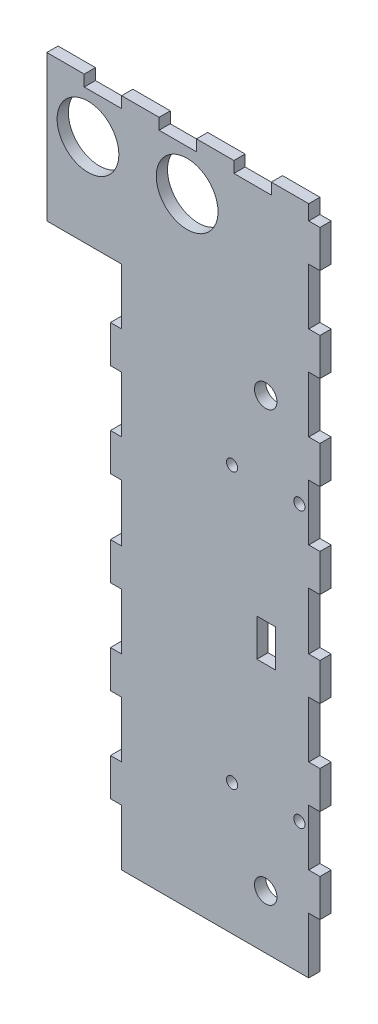
SolidWorks part; units mm, degrees
ref_plane "Plan de face" through (0, 0, 0) normal (0, 0, 1) x (1, 0, 0)
ref_plane "Plan de dessus" through (0, 0, 0) normal (0, 1, 0) x (1, 0, 0)
ref_plane "Plan de droite" through (0, 0, 0) normal (1, 0, 0) x (0, 0, -1)
sketch "Esquisse2" plane through (0, 0, 0) normal (0, 0, 1) x (1, 0, 0)
  line L3 (-71.7115, -86.2767) -> (-71.7115, -71.2767)
  line L4 (-71.7115, -21.2767) -> (-74.7115, -21.2767)
  line L5 (-74.7115, -21.2767) -> (-74.7115, -11.2767)
  line L6 (-74.7115, -11.2767) -> (-71.7115, -11.2767)
  line L7 (-71.7115, -11.2767) -> (-71.7115, 3.9701)
  line L8 (-71.7115, 3.9701) -> (-74.7115, 3.9701)
  line L9 (-74.7115, 3.9701) -> (-74.7115, 13.9701)
  line L10 (-74.7115, 13.9701) -> (-71.7115, 13.9701)
  line L11 (-71.7115, 13.9701) -> (-71.7115, 28.9701)
  line L12 (-71.7115, 28.9701) -> (-74.7115, 28.9701)
  line L13 (-74.7115, 28.9701) -> (-74.7115, 38.9701)
  line L14 (-74.7115, 38.9701) -> (-71.7115, 38.9701)
  line L15 (-71.7115, 38.9701) -> (-71.7115, 53.9701)
  line L16 (-71.7115, -36.2767) -> (-74.7115, -36.2767)
  line L17 (-74.7115, -36.2767) -> (-74.7115, -46.2767)
  line L18 (-74.7115, -46.2767) -> (-71.7115, -46.2767)
  line L19 (-71.7115, -61.2767) -> (-74.7115, -61.2767)
  line L20 (-74.7115, -61.2767) -> (-74.7115, -71.2767)
  line L21 (-74.7115, -71.2767) -> (-71.7115, -71.2767)
  line L22 (-71.7115, -61.2767) -> (-71.7115, -46.2767)
  line L23 (-71.7115, -36.2767) -> (-71.7115, -21.2767)
  line L24 (-71.7115, -86.2767) -> (-21.7115, -86.2767)
  line L26 (-46.7115, 53.7233) -> (-46.7115, -122.9745) construction
  line L27 (-21.7115, -36.2767) -> (-21.7115, -21.2767)
  line L28 (-21.7115, -61.2767) -> (-21.7115, -46.2767)
  line L29 (-18.7115, -71.2767) -> (-21.7115, -71.2767)
  line L30 (-18.7115, -61.2767) -> (-18.7115, -71.2767)
  line L31 (-21.7115, -61.2767) -> (-18.7115, -61.2767)
  line L32 (-18.7115, -46.2767) -> (-21.7115, -46.2767)
  line L33 (-18.7115, -36.2767) -> (-18.7115, -46.2767)
  line L34 (-21.7115, -36.2767) -> (-18.7115, -36.2767)
  line L35 (-21.7115, 38.9701) -> (-21.7115, 53.9701)
  line L36 (-18.7115, 38.9701) -> (-21.7115, 38.9701)
  line L37 (-18.7115, 28.9701) -> (-18.7115, 38.9701)
  line L38 (-21.7115, 28.9701) -> (-18.7115, 28.9701)
  line L39 (-21.7115, 13.9701) -> (-21.7115, 28.9701)
  line L40 (-18.7115, 13.9701) -> (-21.7115, 13.9701)
  line L41 (-18.7115, 3.9701) -> (-18.7115, 13.9701)
  line L42 (-21.7115, 3.9701) -> (-18.7115, 3.9701)
  line L43 (-21.7115, -11.2767) -> (-21.7115, 3.9701)
  line L44 (-18.7115, -11.2767) -> (-21.7115, -11.2767)
  line L45 (-18.7115, -21.2767) -> (-18.7115, -11.2767)
  line L46 (-21.7115, -21.2767) -> (-18.7115, -21.2767)
  line L47 (-21.7115, -86.2767) -> (-21.7115, -71.2767)
  line L48 (-21.7115, 53.9701) -> (-18.7115, 53.9701)
  line L49 (-18.7115, 53.9701) -> (-18.7115, 63.9701)
  line L50 (-18.7115, 63.9701) -> (-21.7115, 63.9701)
  line L51 (-21.7115, 63.9701) -> (-21.7115, 78.9701)
  line L52 (-21.7115, 78.9701) -> (-18.7115, 78.9701)
  line L53 (-18.7115, 78.9701) -> (-18.7115, 88.9701)
  line L54 (-18.7115, 88.9701) -> (-21.7115, 88.9701)
  line L55 (-21.7115, 88.9701) -> (-21.7115, 92.9701)
  line L56 (-21.7115, 92.9701) -> (-31.7115, 92.9701)
  line L58 (-31.7115, 92.9701) -> (-31.7115, 89.9701)
  line L59 (-31.7115, 89.9701) -> (-41.7115, 89.9701)
  line L60 (-41.7115, 89.9701) -> (-41.7115, 92.9701)
  line L61 (-41.7115, 92.9701) -> (-51.7115, 92.9701)
  line L62 (-61.7115, 92.9701) -> (-71.7115, 92.9701)
  line L63 (-91.7115, 92.9701) -> (-91.7115, 53.9701)
  line L64 (-91.7115, 53.9701) -> (-71.7115, 53.9701)
  line L65 (-51.7115, 92.9701) -> (-51.7115, 89.9701)
  line L66 (-51.7115, 89.9701) -> (-61.7115, 89.9701)
  line L67 (-61.7115, 89.9701) -> (-61.7115, 92.9701)
  line L68 (-71.7115, 92.9701) -> (-71.7115, 89.9701)
  line L69 (-71.7115, 89.9701) -> (-81.7115, 89.9701)
  line L70 (-81.7115, 89.9701) -> (-81.7115, 92.9701)
  line L71 (-81.7115, 92.9701) -> (-91.7115, 92.9701)
  line L73 (-30.5789, -9.4196) -> (-35.5789, -9.4196)
  line L74 (-30.5789, -9.4196) -> (-30.5789, -19.4196)
  line L75 (-30.5789, -19.4196) -> (-35.5789, -19.4196)
  line L76 (-35.5789, -9.4196) -> (-35.5789, -19.4196)
  circle A0 centre (-42.2115, -51.2767) radius 1.5
  circle A4 centre (-24.2115, -51.2767) radius 1.5
  circle A10 centre (-33.2115, 42.8233) radius 3
  circle A11 centre (-42.2115, 22.2233) radius 1.5
  circle A12 centre (-24.2115, 22.2233) radius 1.5
  circle A13 centre (-80.7115, 78.9701) radius 8.25
  circle A14 centre (-54.2115, 78.9701) radius 8.25
  circle A15 centre (-33.2115, -71.8767) radius 3
  point P0 (-46.7115, -86.2767)
  point P32 (-46.7115, -86.2767)
  point P34 (-46.7115, -86.2767)
  dimension "D15" = 3
  dimension "D16" = 20.6
  dimension "D34" = 16.5
  dimension "D35" = 16.5
  dimension "D37" = 25
  dimension "D38" = 10
  dimension "D42" = 11.5
  dimension "D44" = 2.5
  dimension "D45" = 11.5
  dimension "D46" = 18
  dimension "D54" = 6
  dimension "D2" = 3
  dimension "D3" = 3
  dimension "D4" = 3
  dimension "D5" = 3
  dimension "D6" = 3
  dimension "D7" = 3
  dimension "D8" = 3
  dimension "D9" = 20
  dimension "D10" = 3
  dimension "D11" = 3
  dimension "D12" = 70
  dimension "D13" = 50
  dimension "D14" = 2.5
  dimension "D18" = 15
  dimension "D19" = 10
  dimension "D20" = 10
  dimension "D21" = 15
  dimension "D22" = 3
  dimension "D23" = 3
  dimension "D24" = 4
  dimension "D25" = 10
  dimension "D26" = 3
  dimension "D27" = 39
  dimension "D28" = 10
  dimension "D29" = 10
  dimension "D30" = 10
  dimension "D31" = 10
  dimension "D32" = 10
  dimension "D33" = 3
  dimension "D36" = 26.5
  dimension "15" = 11
  dimension "D39" = 5
  dimension "D40" = 2.5
  dimension "D41" = 18
  dimension "D43" = 3
  dimension "D47" = 8.8674
  dimension "D48" = 3
  dimension "D49" = 3
  dimension "D50" = 3
  dimension "D51" = 3
  dimension "D52" = 3
  dimension "D53" = 3
extrude "Boss.-Extru.1" add sketch "Esquisse2" along normal blind 3
